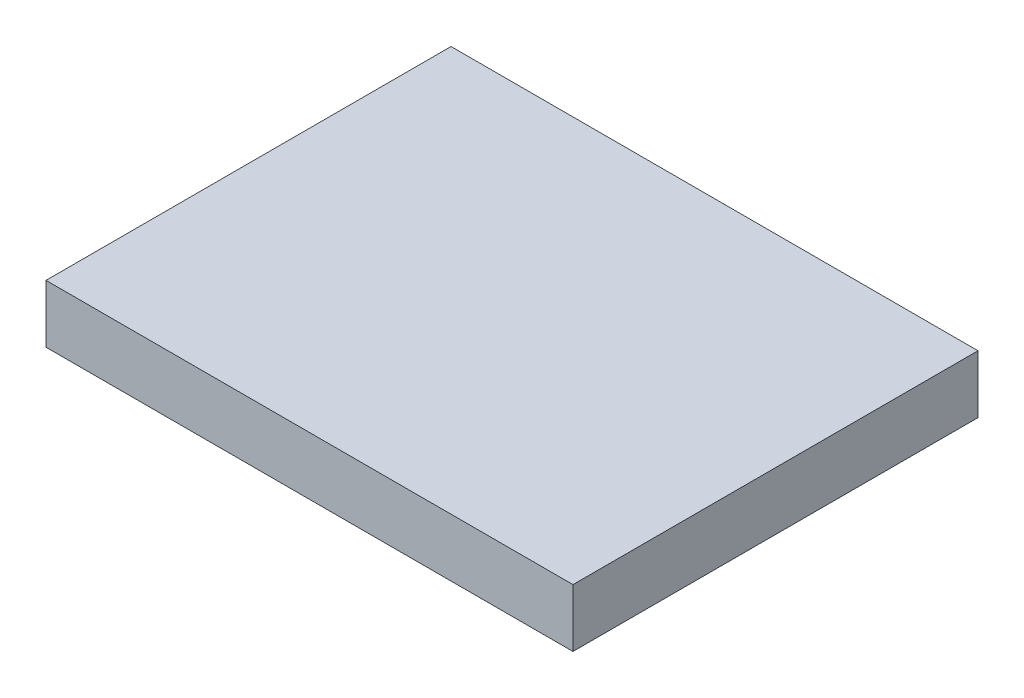
SolidWorks part; units mm, degrees
ref_plane "前视基准面" through (0, 0, 0) normal (0, 0, 1) x (1, 0, 0)
ref_plane "上视基准面" through (0, 0, 0) normal (0, 1, 0) x (1, 0, 0)
ref_plane "右视基准面" through (0, 0, 0) normal (1, 0, 0) x (0, 0, -1)
sketch "草图1" plane through (0, 0, 0) normal (0, 1, 0) x (1, 0, 0)
  line L1 (-45.4831, -34.9591) -> (45.4831, -34.9591)
  line L2 (-45.4831, -34.9591) -> (-45.4831, 34.9591)
  line L3 (-45.4831, 34.9591) -> (45.4831, 34.9591)
  line L4 (45.4831, -34.9591) -> (45.4831, 34.9591)
  line L5 (-45.4831, -34.9591) -> (45.4831, 34.9591) construction
  line L6 (-45.4831, 34.9591) -> (45.4831, -34.9591) construction
  point P0 (0, 0)
extrude "凸台-拉伸1" add sketch "草图1" along normal blind 10
